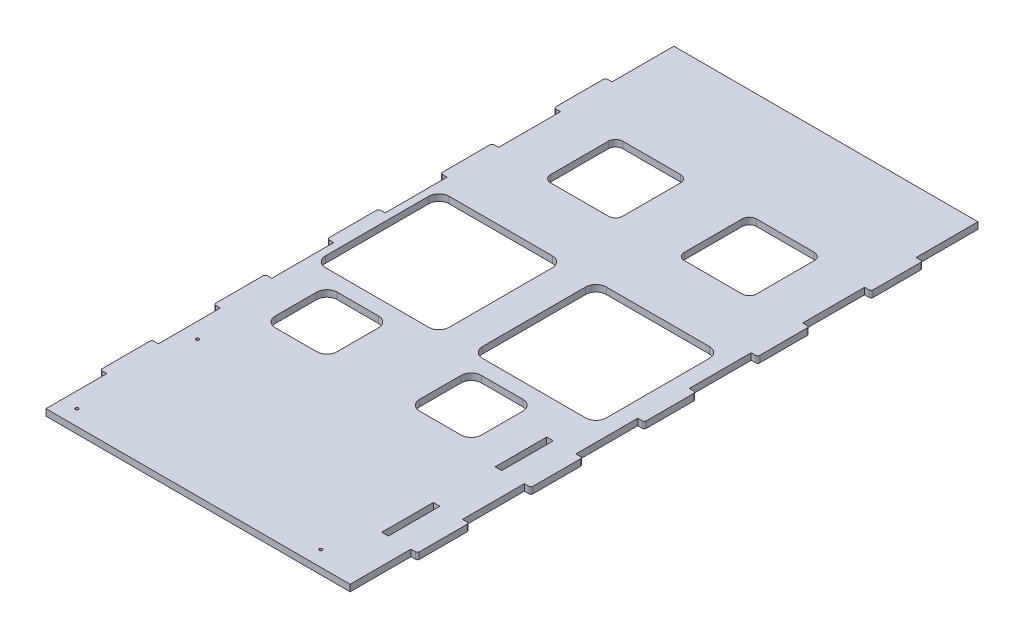
SolidWorks part; units mm, degrees
material "Beech"
ref_plane "Front Plane" through (0, 0, 0) normal (0, 0, 1) x (1, 0, 0)
ref_plane "Top Plane" through (0, 0, 0) normal (0, 1, 0) x (1, 0, 0)
ref_plane "Right Plane" through (0, 0, 0) normal (1, 0, 0) x (0, 0, -1)
sketch "Sketch1" plane through (0, 0, 0) normal (0, 1, 0) x (1, 0, 0)
  line L1 (0, 0) -> (295, 0)
  line L2 (0, 0) -> (0, 59)
  line L3 (0, 609) -> (295, 609)
  line L4 (295, 0) -> (295, 59)
  line L5 (0, 59) -> (-6.35, 59)
  line L7 (0, 109) -> (-6.35, 109)
  line L8 (-6.35, 59) -> (-6.35, 109)
  line L9 (0, 169) -> (-6.35, 169)
  line L10 (-6.35, 169) -> (-6.35, 219)
  line L11 (0, 219) -> (-6.35, 219)
  line L13 (0, 279) -> (-6.35, 279)
  line L14 (-6.35, 279) -> (-6.35, 329)
  line L15 (0, 329) -> (-6.35, 329)
  line L17 (0, 389) -> (-6.35, 389)
  line L18 (-6.35, 389) -> (-6.35, 439)
  line L19 (0, 439) -> (-6.35, 439)
  line L21 (0, 499) -> (-6.35, 499)
  line L22 (-6.35, 499) -> (-6.35, 549)
  line L23 (0, 549) -> (-6.35, 549)
  line L25 (295, 59) -> (301.35, 59)
  line L27 (295, 109) -> (301.35, 109)
  line L28 (301.35, 59) -> (301.35, 109)
  line L29 (295, 169) -> (301.35, 169)
  line L30 (301.35, 169) -> (301.35, 219)
  line L31 (295, 219) -> (301.35, 219)
  line L33 (295, 279) -> (301.35, 279)
  line L34 (301.35, 279) -> (301.35, 329)
  line L35 (295, 329) -> (301.35, 329)
  line L37 (295, 389) -> (301.35, 389)
  line L38 (301.35, 389) -> (301.35, 439)
  line L39 (295, 439) -> (301.35, 439)
  line L41 (295, 499) -> (301.35, 499)
  line L42 (301.35, 499) -> (301.35, 549)
  line L43 (295, 549) -> (301.35, 549)
  line L44 (0, 549) -> (0, 609)
  line L46 (0, 329) -> (0, 389)
  line L49 (0, 219) -> (0, 279)
  line L50 (0, 109) -> (0, 169)
  line L51 (295, 109) -> (295, 169)
  line L52 (295, 219) -> (295, 279)
  line L53 (295, 329) -> (295, 389)
  line L54 (295, 439) -> (295, 499)
  line L55 (295, 549) -> (295, 609)
  line L56 (0, 439) -> (0, 499)
  dimension "D1" = 609
  dimension "D2" = 295
  dimension "D3" = 6.35
  dimension "D4" = 50
  dimension "D5" = 59
  dimension "D7" = 60
  dimension "D8" = 50
  dimension "D9" = 6.35
  dimension "D11" = 59
  dimension "D12" = 60
  dimension "D6" = 5
  dimension "D10" = 5
extrude "Boss-Extrude1" add sketch "Sketch1" along normal blind 6.35
fillet "Fillet1" radius 2 20 edges at (301.35, 3.175, -549) (301.35, 3.175, -499) (301.35, 3.175, -439) (301.35, 3.175, -389) (301.35, 3.175, -329) (301.35, 3.175, -279) (301.35, 3.175, -219) (301.35, 3.175, -169) (301.35, 3.175, -109) (301.35, 3.175, -59) (-6.35, 3.175, -59) (-6.35, 3.175, -109) (-6.35, 3.175, -169) (-6.35, 3.175, -219) (-6.35, 3.175, -279) (-6.35, 3.175, -329) (-6.35, 3.175, -389) (-6.35, 3.175, -439) (-6.35, 3.175, -499) (-6.35, 3.175, -549)
sketch "Sketch2" plane through (0, 6.35, 0) normal (0, 1, 0) x (1, 0, 0)
  line L0 (266.65, 0) -> (266.65, 100) construction
  line L1 (0, 0) -> (295, 0) construction
  line L2 (0, 609) -> (0, 0) construction
  line L3 (295, 609) -> (295, 0) construction
  line L4 (0, 150) -> (266.65, 100) construction
  line L5 (266.65, 169) -> (266.65, 219)
  line L6 (266.65, 59) -> (273, 59)
  line L7 (266.65, 59) -> (266.65, 109)
  line L8 (266.65, 109) -> (273, 109)
  line L9 (273, 59) -> (273, 109)
  line L10 (266.65, 169) -> (273, 169)
  line L11 (273, 169) -> (273, 219)
  line L12 (266.65, 219) -> (273, 219)
  line L13 (0, 84.2124) -> (266.65, 84) construction
  line L14 (55.0424, 504.4355) -> (111.0424, 504.4355)
  line L15 (48.0424, 497.4355) -> (48.0424, 441.4355)
  line L16 (55.0424, 434.4355) -> (111.0424, 434.4355)
  line L17 (118.0424, 497.4355) -> (118.0424, 441.4355)
  line L18 (185.2335, 503.9695) -> (241.2335, 503.9695)
  line L19 (178.2335, 496.9695) -> (178.2335, 440.9695)
  line L20 (185.2335, 433.9695) -> (241.2335, 433.9695)
  line L21 (248.2335, 496.9695) -> (248.2335, 440.9695)
  line L22 (43.325, 239.1432) -> (83.325, 239.1432)
  line L23 (33.325, 229.1432) -> (33.325, 189.1432)
  line L24 (43.325, 179.1432) -> (83.325, 179.1432)
  line L25 (93.325, 229.1432) -> (93.325, 189.1432)
  line L26 (33.325, 239.1432) -> (93.325, 179.1432) construction
  line L27 (33.325, 179.1432) -> (93.325, 239.1432) construction
  line L32 (133.325, 0) -> (133.325, 609) construction
  line L33 (295, 609) -> (0, 609) construction
  line L34 (7.1727, 373.9596) -> (127.1727, 373.9596)
  line L35 (7.1727, 373.9596) -> (7.1727, 253.9596)
  line L36 (7.1727, 253.9596) -> (127.1727, 253.9596)
  line L37 (127.1727, 373.9596) -> (127.1727, 253.9596)
  line L38 (159.4648, 373.9596) -> (279.4648, 373.9596)
  line L39 (159.4648, 373.9596) -> (159.4648, 253.9596)
  line L40 (159.4648, 253.9596) -> (279.4648, 253.9596)
  line L41 (279.4648, 373.9596) -> (279.4648, 253.9596)
  line L42 (233.325, 179.1432) -> (173.325, 239.1432) construction
  line L43 (233.325, 239.1432) -> (173.325, 179.1432) construction
  line L44 (173.325, 229.1432) -> (173.325, 189.1432)
  line L45 (223.325, 179.1432) -> (183.325, 179.1432)
  line L46 (233.325, 229.1432) -> (233.325, 189.1432)
  line L47 (223.325, 239.1432) -> (183.325, 239.1432)
  arc A0 (48.0424, 441.4355) -> (55.0424, 434.4355) centre (55.0424, 441.4355) ccw
  arc A1 (111.0424, 434.4355) -> (118.0424, 441.4355) centre (111.0424, 441.4355) ccw
  arc A2 (111.0424, 504.4355) -> (118.0424, 497.4355) centre (111.0424, 497.4355) cw
  arc A3 (55.0424, 504.4355) -> (48.0424, 497.4355) centre (55.0424, 497.4355) ccw
  arc A4 (178.2335, 440.9695) -> (185.2335, 433.9695) centre (185.2335, 440.9695) ccw
  arc A5 (241.2335, 433.9695) -> (248.2335, 440.9695) centre (241.2335, 440.9695) ccw
  arc A6 (241.2335, 503.9695) -> (248.2335, 496.9695) centre (241.2335, 496.9695) cw
  arc A7 (185.2335, 503.9695) -> (178.2335, 496.9695) centre (185.2335, 496.9695) ccw
  arc A8 (33.325, 189.1432) -> (43.325, 179.1432) centre (43.325, 189.1432) ccw
  arc A9 (83.325, 179.1432) -> (93.325, 189.1432) centre (83.325, 189.1432) ccw
  arc A10 (83.325, 239.1432) -> (93.325, 229.1432) centre (83.325, 229.1432) cw
  arc A11 (43.325, 239.1432) -> (33.325, 229.1432) centre (43.325, 229.1432) ccw
  arc A16 (223.325, 239.1432) -> (233.325, 229.1432) centre (223.325, 229.1432) cw
  arc A17 (183.325, 239.1432) -> (173.325, 229.1432) centre (183.325, 229.1432) ccw
  arc A18 (183.325, 179.1432) -> (173.325, 189.1432) centre (183.325, 189.1432) cw
  arc A19 (233.325, 189.1432) -> (223.325, 179.1432) centre (223.325, 189.1432) cw
  circle A20 centre (15, 15) radius 1.5
  circle A21 centre (251.65, 15) radius 1.5
  circle A22 centre (15, 131.9259) radius 1.5
  point P33 (118.0424, 434.4355)
  point P36 (118.0424, 504.4355)
  point P39 (48.0424, 504.4355)
  point P42 (178.2335, 433.9695)
  point P47 (248.2335, 503.9695)
  point P50 (178.2335, 503.9695)
  point P51 (63.325, 209.1432)
  point P74 (133.325, 84.1062)
  point P99 (203.325, 209.1432)
  dimension "D10" = 7
  dimension "D11" = 7
  dimension "D16" = 10
  dimension "D17" = 70
  dimension "D22" = 3
  dimension "D25" = 3
  dimension "D28" = 3
  dimension "D1" = 100
  dimension "D2" = 150
  dimension "D3" = 6.35
  dimension "D4" = 50
  dimension "D6" = 70
  dimension "D7" = 70
  dimension "D8" = 70
  dimension "D9" = 70
  dimension "D12" = 60
  dimension "D13" = 60
  dimension "D14" = 22
  dimension "D15" = 59
  dimension "12" = 120
  dimension "D19" = 120
  dimension "D20" = 120
  dimension "D21" = 120
  dimension "D23" = 15
  dimension "D24" = 15
  dimension "D26" = 15
  dimension "D27" = 15
  dimension "D29" = 15
  dimension "D30" = 15
  dimension "D5" = 2
extrude "Cut-Extrude1" cut sketch "Sketch2" against normal blind 6.35
fillet "Fillet2" radius 10 8 edges at (127.1727, 3.175, -253.9596) (7.1727, 3.175, -253.9596) (7.1727, 3.175, -373.9596) (127.1727, 3.175, -373.9596) (159.4648, 3.175, -253.9596) (279.4648, 3.175, -253.9596) (279.4648, 3.175, -373.9596) (159.4648, 3.175, -373.9596)
